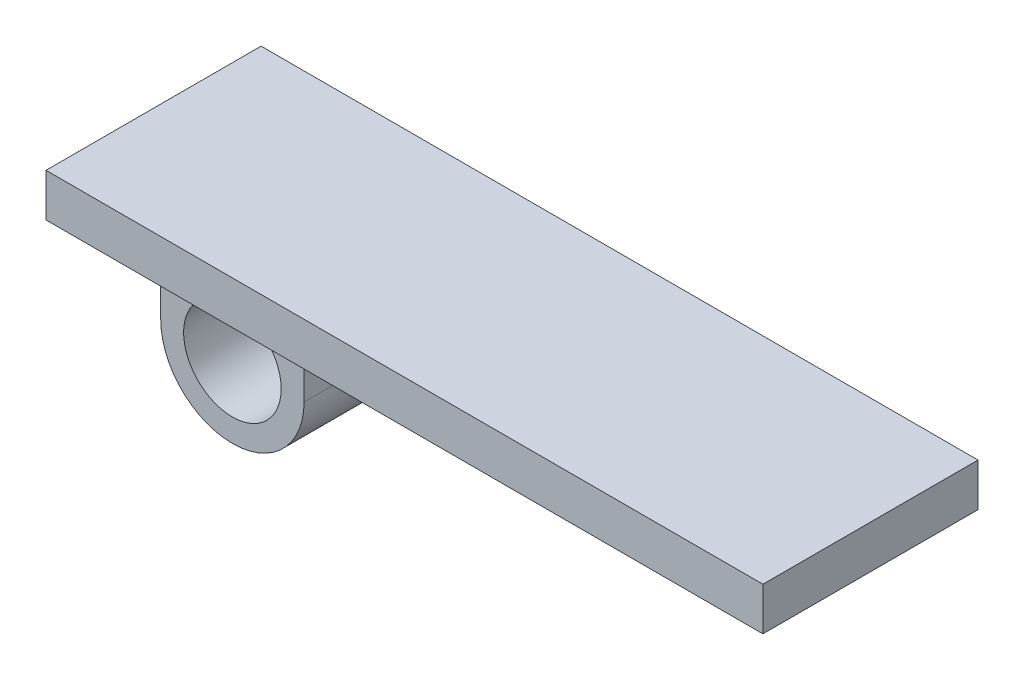
SolidWorks part; units mm, degrees
ref_plane "前视基准面" through (0, 0, 0) normal (0, 0, 1) x (1, 0, 0)
ref_plane "上视基准面" through (0, 0, 0) normal (0, 1, 0) x (1, 0, 0)
ref_plane "右视基准面" through (0, 0, 0) normal (1, 0, 0) x (0, 0, -1)
other "Configuration Table"
sketch "草图1" plane through (0, 0, 0) normal (0, 0, 1) x (1, 0, 0)
  line L0 (0, 0) -> (0, 10) construction
  line L1 (-5, 0) -> (-5, 10)
  line L2 (5, 0) -> (5, 10)
  line L3 (-5, 10) -> (5, 10)
  arc A0 (-5, 0) -> (5, 0) centre (0, 0) ccw
  arc A1 (5, 10) -> (-5, 10) centre (0, 10) ccw
  circle A2 centre (0, 0) radius 3.4
  point P3 (0, 5)
  dimension "D1" = 5
  dimension "D2" = 6.8
  dimension "D3" = 10
extrude "凸台-拉伸1" add sketch "草图1" along normal blind 7
sketch "草图2" plane through (0, 10, 0) normal (0, 1, 0) x (1, 0, 0)
  line L0 (-5, 0) -> (5, 0) construction
  line L1 (45, 0) -> (-5, 0)
  line L3 (45, -15) -> (-5, -15)
  line L4 (-5, 0) -> (-5, -15)
  line L6 (-5, -7) -> (-5, 0) construction
  line L7 (45, -15) -> (45, 0)
  dimension "D1" = 15
  dimension "D2" = 50
extrude "凸台-拉伸2" add sketch "草图2" along normal blind 3 contours L1 L4 L3 L7
